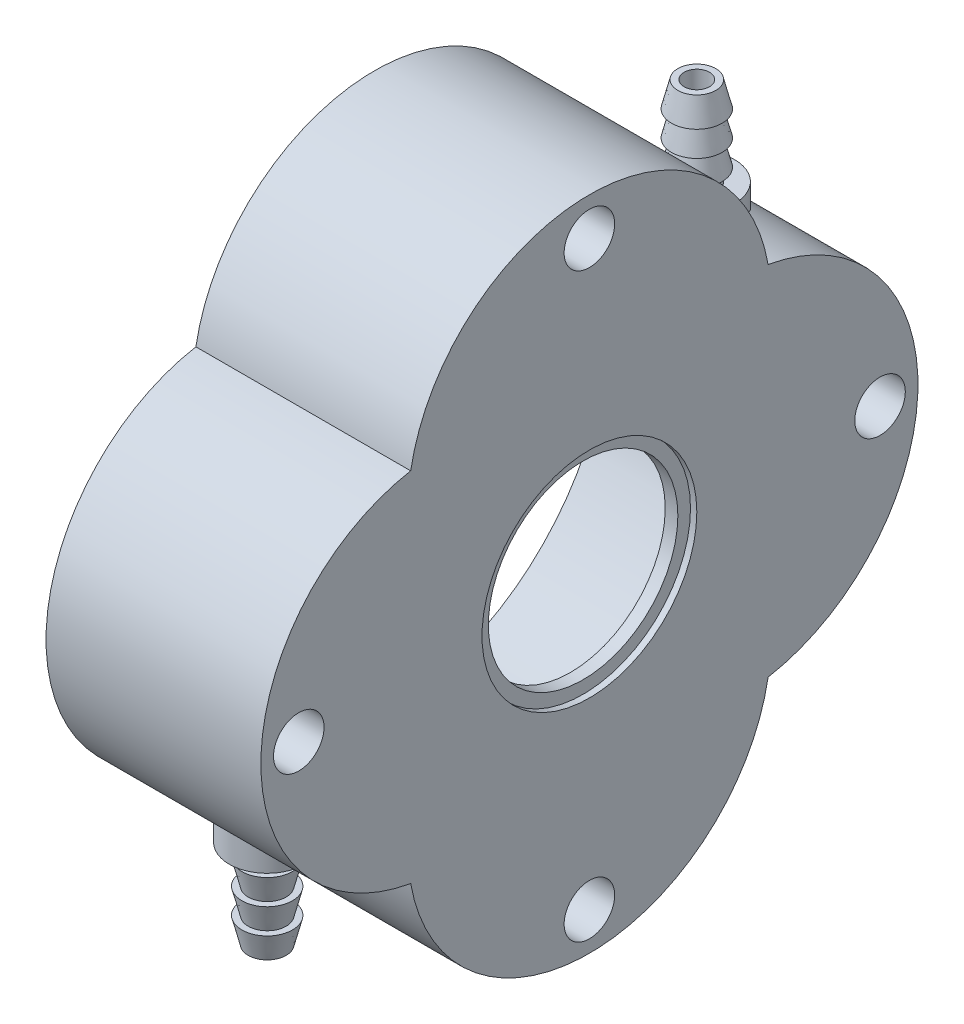
SolidWorks part; units mm, degrees
ref_plane "Front Plane" through (0, 0, 0) normal (0, 0, 1) x (1, 0, 0)
ref_plane "Top Plane" through (0, 0, 0) normal (0, 1, 0) x (1, 0, 0)
ref_plane "Right Plane" through (0, 0, 0) normal (1, 0, 0) x (0, 0, -1)
sketch "Sketch2" plane through (0, 0, 0) normal (1, 0, 0) x (0, 0, -1)
  line L1 (-14.1421, -14.1421) -> (14.1421, -14.1421) construction
  line L2 (-14.1421, -14.1421) -> (-14.1421, 14.1421) construction
  line L3 (-14.1421, 14.1421) -> (14.1421, 14.1421) construction
  line L4 (14.1421, -14.1421) -> (14.1421, 14.1421) construction
  circle A1 centre (0, 23) radius 2
  circle A2 centre (23, 0) radius 2
  circle A3 centre (0, -23) radius 2
  circle A4 centre (-23, 0) radius 2
  circle A5 centre (0, 0) radius 7.5 construction
  circle A6 centre (0, 0) radius 8.5 construction
  circle A10 centre (0, 0) radius 18 construction
  circle A11 centre (0, 0) radius 26 construction
  circle A12 centre (0, -23) radius 3 construction
  circle A14 centre (23, 0) radius 3 construction
  arc A25 (-14.1421, 14.1421) -> (-14.1421, -14.1421) centre (-11.6378, 0) ccw
  arc A26 (-14.1421, -14.1421) -> (14.1421, -14.1421) centre (0, -11.6378) ccw
  circle A27 centre (0, 0) radius 20 construction
  arc A28 (14.1421, 14.1421) -> (-14.1421, 14.1421) centre (0, 11.6378) ccw
  arc A29 (14.1421, -14.1421) -> (14.1421, 14.1421) centre (11.6378, 0) ccw
  point P14 (0, 0)
  point P36 (0, 0)
  point P49 (0, 0)
  dimension "D1" = 36
  dimension "D3" = 4
  dimension "D5" = 15
  dimension "D6" = 17
  dimension "D7" = 52
  dimension "D8" = 40
  dimension "D4" = 23
  dimension "D2" = 4
  dimension "D9" = 4
extrude "Body" add sketch "Sketch2" along normal mid plane 17
sketch "Sketch10" plane through (8.5, 0, 0) normal (1, 0, 0) x (0, 0, -1)
  circle A0 centre (0, 0) radius 7.5
  dimension "D1" = 15
extrude "Cut-Extrude2" cut sketch "Sketch10" against normal blind 10
sketch "Sketch3" plane through (8.5, 0, 0) normal (1, 0, 0) x (0, 0, -1)
  circle A0 centre (0, 0) radius 8.5
  dimension "D1" = 17
extrude "O-Ring Seat" cut sketch "Sketch3" against normal blind 0.5
sketch "Sketch8" plane through (0, 0, 0) normal (-1, 0, 0) x (0, 0, 1)
  circle A0 centre (0, 0) radius 18
  dimension "D1" = 36
extrude "Cavity" cut sketch "Sketch8" against normal mid plane 14
sketch "Sketch5" plane through (0, 0, 0) normal (0, 1, 0) x (1, 0, 0)
  line L1 (0, -28.6) -> (0, 28.6) construction
  circle A0 centre (0, 17) radius 1
  dimension "D1" = 2
  dimension "D2" = 17
extrude "Outlet" cut sketch "Sketch5" along normal through all
ref_plane "Plane2" through (0, 14.1421, 0) normal (0, 1, 0) x (1, 0, 0)
sketch "Sketch6" plane through (0, 14.1421, 0) normal (0, 1, 0) x (1, 0, 0)
  circle A2 centre (0, 17) radius 1
  circle A3 centre (0, 17) radius 3
  dimension "D1" = 2
extrude "Boss-Extrude2" add sketch "Sketch6" against normal up to next
ref_axis "Axis1" through (0, 14.1421, -17) along (0, -1, 0)
sketch "Sketch9" plane through (0, 0, 0) normal (1, 0, 0) x (0, 0, -1)
  line L0 (18, 14.1421) -> (18, 21.1421)
  line L1 (18, 21.1421) -> (18.5, 21.1421)
  line L2 (18.5, 21.1421) -> (19, 19.1421)
  line L3 (19, 19.1421) -> (18.5, 19.1421)
  line L4 (18.5, 19.1421) -> (19, 17.1421)
  line L5 (19, 17.1421) -> (18.5, 17.1421)
  line L6 (18.5, 17.1421) -> (19, 15.1421)
  line L7 (19, 15.1421) -> (18.5, 15.1421)
  line L8 (18.5, 15.1421) -> (18.5, 14.1421)
  line L9 (18.5, 14.1421) -> (18, 14.1421)
  line L10 (17, 14.1421) -> (17, -0.6906) construction
  line L11 (20, 14.1421) -> (14.1421, 14.1421) construction
  dimension "D1" = 0.5
  dimension "D2" = 0.5
  dimension "D3" = 2
  dimension "D4" = 1
  dimension "D5" = 1
revolve "Revolve1" add sketch "Sketch9" angle 360 about axis through (0, 14.1421, -17) along (0, -1, 0)
pattern_circular "Inlet" count 2 every 180 about axis through (8, 0, 0) along (1, 0, 0) of "Boss-Extrude2", "Revolve1", "Outlet"
sketch "Sketch11" plane through (-8.5, 0, 0) normal (-1, 0, 0) x (0, 0, 1)
  circle A0 centre (0, 0) radius 18
  dimension "D1" = 36
extrude "Cut-Extrude3" cut sketch "Sketch11" against normal up to next
sketch "Sketch12" plane through (-8.5, 0, 0) normal (-1, 0, 0) x (0, 0, 1)
  circle A0 centre (0, 0) radius 19.5
  dimension "D1" = 39
extrude "Cut-Extrude4" cut sketch "Sketch12" against normal blind 0.5
